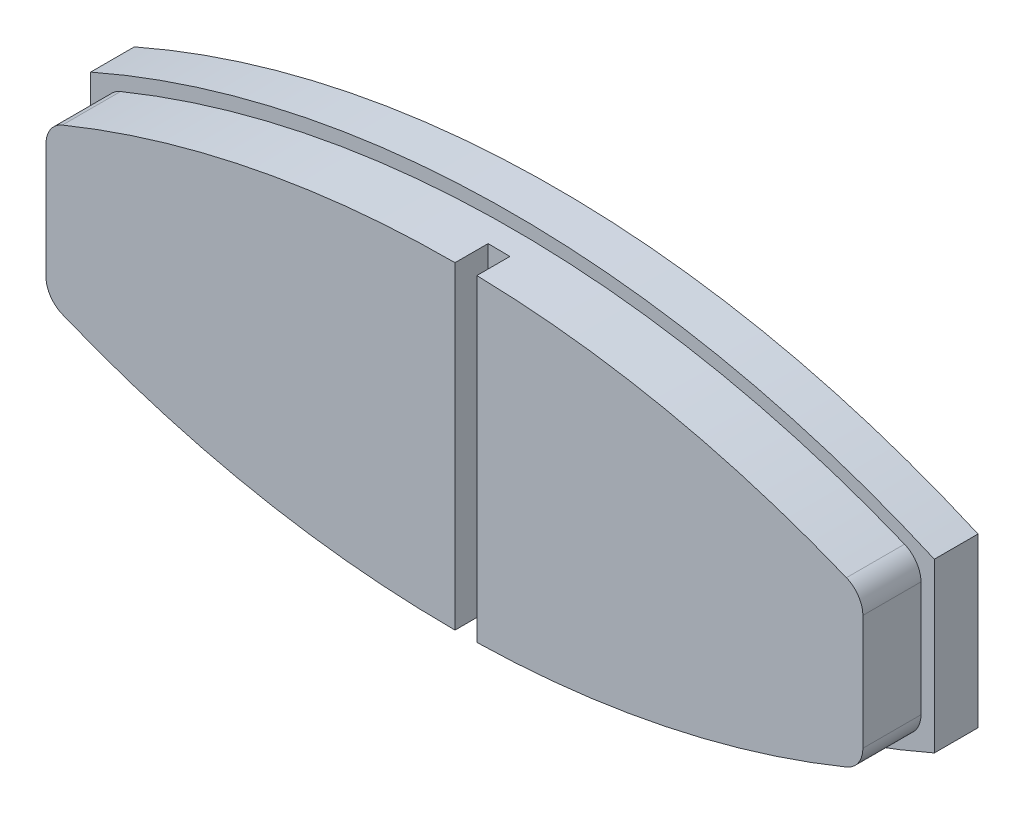
SolidWorks part; units mm, degrees
ref_plane "Front Plane" through (0, 0, 0) normal (0, 0, 1) x (1, 0, 0)
ref_plane "Top Plane" through (0, 0, 0) normal (0, 1, 0) x (1, 0, 0)
ref_plane "Right Plane" through (0, 0, 0) normal (1, 0, 0) x (0, 0, -1)
sketch "Sketch1" plane through (0, 0, 0) normal (0, 0, 1) x (1, 0, 0)
  line L0 (-31.9214, 6.35) -> (-31.9214, -6.35)
  line L1 (0, 0) -> (-17.9324, 0) construction
  line L2 (0, 0) -> (0, 13.0556) construction
  line L3 (31.9214, 6.35) -> (31.9214, -6.35)
  arc A0 (31.9214, 6.35) -> (-31.9214, 6.35) centre (0, -66.2769) ccw
  arc A1 (31.9214, -6.35) -> (-31.9214, -6.35) centre (0, 66.2769) cw
  point P8 (-31.9214, 0)
  dimension "D3" = 31.9214
  dimension "D1" = 13.0556
  dimension "D2" = 12.7
extrude "Boss-Extrude1" add sketch "Sketch1" along normal blind 3.302
sketch "Sketch2" plane through (0, 0, 3.302) normal (0, 0, 1) x (1, 0, 0)
  line L4 (-30.9054, 5.6837) -> (-30.9055, -5.6837)
  line L5 (30.9054, -5.6837) -> (30.9054, 5.6837)
  line L6 (-30.9054, 5.6837) -> (-30.9055, -5.6837)
  line L7 (30.9054, -5.6837) -> (30.9054, 5.6837)
  arc A4 (30.9054, 5.6837) -> (-30.9054, 5.6837) centre (0, -66.2769) ccw
  arc A5 (-30.9055, -5.6837) -> (30.9054, -5.6837) centre (0, 66.2769) ccw
  arc A6 (30.9054, 5.6837) -> (-30.9054, 5.6837) centre (0, -66.2769) ccw
  arc A7 (-30.9055, -5.6837) -> (30.9054, -5.6837) centre (0, 66.2769) ccw
  dimension "D1" = 1.016
extrude "Boss-Extrude2" add sketch "Sketch2" along normal blind 4.3942 separate body
sketch "Sketch3" plane through (0, 0, 0) normal (0, 0, -1) x (-1, 0, 0)
  line L0 (0, 0) -> (0, 8.5723) construction
  circle A0 centre (-23.8125, 0) radius 3.35
  circle A1 centre (23.8125, 0) radius 3.35
  dimension "D1" = 6.7
  dimension "D2" = 23.8125
extrude "Cut-Extrude1" cut sketch "Sketch3" against normal blind 6.35
sketch "Sketch6" plane through (0, 0, 7.6962) normal (0, 0, 1) x (1, 0, 0)
  line L0 (30.9054, -5.6837) -> (30.9054, 5.6837) construction
  line L1 (0.0445, 18.5168) -> (1.6955, 18.5168)
  line L2 (0.0445, 18.5168) -> (0.0445, -19.1088)
  line L3 (0.0445, -19.1088) -> (1.6955, -19.1088)
  line L4 (1.6955, 18.5168) -> (1.6955, -19.1088)
  dimension "D1" = 1.651
  dimension "D2" = 29.21
extrude "Cut-Extrude2" cut sketch "Sketch6" against normal blind 2.5
fillet "Fillet1" radius 2 4 edges at (-30.9055, -5.6837, 5.4991) (-30.9054, 5.6837, 5.4991) (30.9054, 5.6837, 5.4991) (30.9054, -5.6837, 5.4991)
sketch "Sketch7" plane through (0, 0, 3.302) normal (0, 0, 1) x (1, 0, 0)
  line L0 (0.87, 12.0348) -> (0.87, 13.6223) construction
  line L1 (0.87, 13.6223) -> (0.87, -100.6777) construction
  arc A0 (1.6955, 12.0212) -> (0.0445, 12.0396) centre (0, -66.2769) ccw construction
  circle A1 centre (0.87, -100.6777) radius 114.3
  dimension "D1" = 1.5875
  dimension "D2" = 114.3
sketch "Sketch8" plane through (0, 0, 3.302) normal (0, 0, 1) x (1, 0, 0)
  line L0 (0.87, 12.0348) -> (0.87, 13.0508) construction
  line L1 (0.87, 13.0508) -> (0.87, -148.2392) construction
  arc A0 (1.6955, 12.0212) -> (0.0445, 12.0396) centre (0, -66.2769) ccw construction
  circle A1 centre (0.87, -148.2392) radius 161.29
  dimension "D1" = 1.016
  dimension "D2" = 161.29
